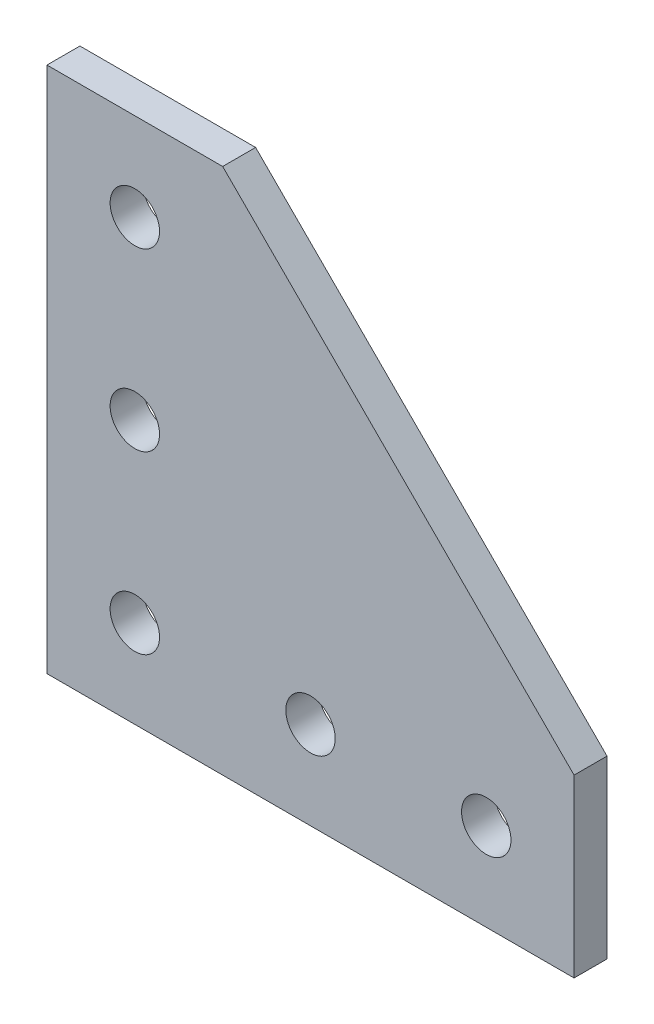
SolidWorks part; units mm, degrees
material "6061 Alloy"
ref_plane "Front Plane" through (0, 0, 0) normal (0, 0, 1) x (1, 0, 0)
ref_plane "Top Plane" through (0, 0, 0) normal (0, 1, 0) x (1, 0, 0)
ref_plane "Right Plane" through (0, 0, 0) normal (1, 0, 0) x (0, 0, -1)
sketch "Sketch1" plane through (0, 0, 0) normal (0, 0, 1) x (1, 0, 0)
  line L0 (0, 0) -> (0, 76.2)
  line L1 (12.7, 12.7) -> (38.1, 12.7) construction
  line L2 (38.1, 12.7) -> (63.5, 12.7) construction
  line L3 (12.7, 12.7) -> (12.7, 38.1) construction
  line L4 (76.2, 25.4) -> (25.4, 76.2)
  line L5 (76.2, 0) -> (0, 0)
  line L6 (12.7, 38.1) -> (12.7, 63.5) construction
  line L7 (76.2, 25.4) -> (76.2, 0)
  line L8 (0, 76.2) -> (25.4, 76.2)
  circle A0 centre (12.7, 12.7) radius 3.2639
  circle A1 centre (38.1, 12.7) radius 3.2639
  circle A2 centre (63.5, 12.7) radius 3.2639
  circle A3 centre (12.7, 38.1) radius 3.2639
  circle A4 centre (12.7, 63.5) radius 3.2639
  dimension "D1" = 25.4
  dimension "E" = 6.5278
  dimension "D2" = 12.7
  dimension "C" = 25.4
  dimension "D3" = 12.7
  dimension "B" = 76.2
extrude "Boss-Extrude1" add sketch "Sketch1" along normal mid plane 4.7625
hole_wizard "1/4 Clearance Hole1" positions "Sketch2" profile "Sketch3" hole size "1/4" standard "ANSI Inch" end condition through all
sketch "Sketch2" plane through (0, 0, 2.3813) normal (0, 0, 1) x (1, 0, 0)
  point P0 (12.7, 63.5)
  point P3 (12.7, 38.1)
  point P6 (12.7, 12.7)
  point P9 (38.1, 12.7)
  point P12 (63.5, 12.7)
sketch "Sketch3" plane through (12.7, 63.5, 2.3813) normal (1, 0, 0) x (0, -1, 0)
  line L0 (0, 0) -> (0, 4.7625)
  line L1 (0, 4.7625) -> (3.5712, 4.7625)
  line L2 (3.5712, 4.7625) -> (3.5712, 0)
  line L5 (3.5712, 0) -> (0, 0)
  line L11 (0, -6.35) -> (0, 107.95) construction
  dimension "Thru Hole Dia." = 7.1425
  dimension "Thru Hole Depth" = 4.7625
